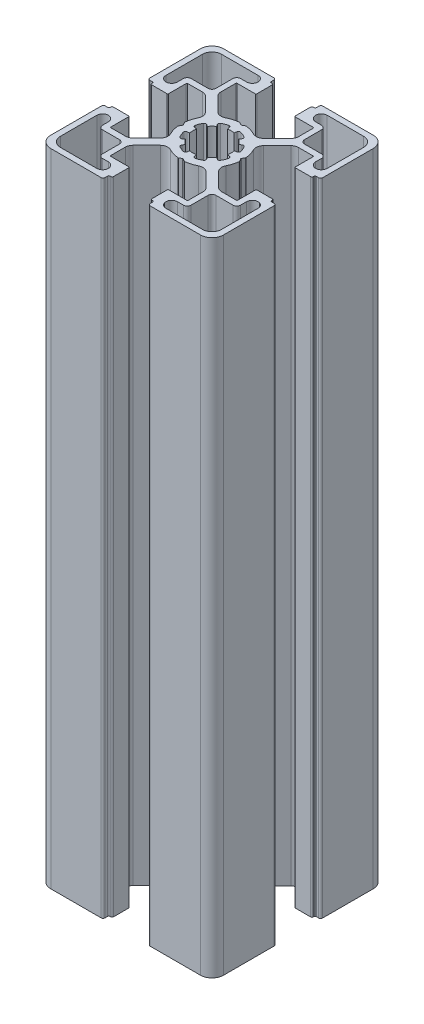
SolidWorks part; units mm, degrees
ref_plane "Front Plane" through (0, 0, 0) normal (0, 0, 1) x (1, 0, 0)
ref_plane "Top Plane" through (0, 0, 0) normal (0, 1, 0) x (1, 0, 0)
ref_plane "Right Plane" through (0, 0, 0) normal (1, 0, 0) x (0, 0, -1)
sketch "Sketch1" plane through (0, 0, 0) normal (0, 1, 0) x (1, 0, 0)
  line L106 (-18, 9.0002) -> (-18, 10.55)
  line L107 (-21, 18.5) -> (-21, 9.0002)
  line L108 (-9, 21) -> (-18.5, 21)
  line L109 (-10.55, 18) -> (-9, 18)
  line L110 (0.9675, 5.4811) -> (0.8674, 4.9242)
  line L111 (2.864, 4.0985) -> (3.1913, 4.5626)
  line L112 (4.5668, 3.2081) -> (4.0897, 2.8765)
  line L113 (4.9205, 0.8878) -> (5.4897, 0.9862)
  line L114 (5.4898, -0.9862) -> (4.9205, -0.8878)
  line L115 (4.0897, -2.8765) -> (4.5668, -3.2082)
  line L116 (3.1914, -4.5627) -> (2.864, -4.0985)
  line L117 (0.8674, -4.9242) -> (0.9675, -5.4811)
  line L118 (-0.9675, -5.4811) -> (-0.8674, -4.9242)
  line L119 (-2.864, -4.0985) -> (-3.1913, -4.5626)
  line L120 (-4.5668, -3.2082) -> (-4.0897, -2.8765)
  line L121 (-4.9205, -0.8878) -> (-5.4897, -0.9862)
  line L122 (-5.4899, 0.9862) -> (-4.9205, 0.8878)
  line L123 (-4.0897, 2.8765) -> (-4.5668, 3.2081)
  line L124 (-3.1914, 4.5627) -> (-2.864, 4.0985)
  line L125 (-0.8674, 4.9242) -> (-0.9675, 5.4811)
  line L126 (-11.55, 12.55) -> (-11.55, 17)
  line L127 (-17, 11.55) -> (-12.55, 11.55)
  line L128 (-21, -9.0002) -> (-21, -18.5)
  line L129 (-18, -10.55) -> (-18, -9.0002)
  line L130 (-12.55, -11.55) -> (-17, -11.55)
  line L131 (-11.55, -17) -> (-11.55, -12.55)
  line L132 (-9, -18) -> (-10.55, -18)
  line L133 (-18.5, -21) -> (-9, -21)
  line L134 (21, 9.0002) -> (21, 18.5)
  line L135 (18, 10.55) -> (18, 9.0002)
  line L136 (12.55, 11.55) -> (17, 11.55)
  line L137 (11.55, 17) -> (11.55, 12.55)
  line L138 (9, 18) -> (10.55, 18)
  line L139 (18.5, 21) -> (9, 21)
  line L140 (17, -11.55) -> (12.55, -11.55)
  line L141 (18, -9.0002) -> (18, -10.55)
  line L142 (21, -18.5) -> (21, -9.0002)
  line L143 (9, -21) -> (18.5, -21)
  line L144 (10.55, -18) -> (9, -18)
  line L145 (11.55, -12.55) -> (11.55, -17)
  line L146 (7.5635, 5.8587) -> (11.1298, 9.425)
  line L147 (12.5048, 9.9945) -> (16.3169, 9.9945)
  line L148 (16.5169, 9.7945) -> (16.5169, 5.2)
  line L149 (16.7169, 5) -> (20.7196, 5)
  line L150 (21.0196, 5.3) -> (21.0196, 5.5)
  line L151 (21.3196, 5.8) -> (22, 5.8)
  line L152 (22.5, 6.3) -> (22.5, 19.5)
  line L153 (19.5, 22.5) -> (6.3757, 22.5)
  line L154 (5.8757, 22) -> (5.8757, 21.3)
  line L155 (5.5757, 21) -> (5.3, 21)
  line L156 (5, 20.7) -> (5, 16.6668)
  line L157 (5.2, 16.4668) -> (9.9054, 16.4668)
  line L158 (10.1054, 16.2668) -> (10.1054, 12.4716)
  line L159 (9.5196, 11.0574) -> (5.9449, 7.4827)
  line L160 (0.7548, 7.9748) -> (0.1126, 7.6069)
  line L161 (-0.1126, 7.6069) -> (-0.7547, 7.9748)
  line L162 (-5.9449, 7.4827) -> (-9.5196, 11.0574)
  line L163 (-10.1054, 12.4716) -> (-10.1054, 16.2668)
  line L164 (-9.9054, 16.4668) -> (-5.2, 16.4668)
  line L165 (-5, 16.6668) -> (-5, 20.7)
  line L166 (-5.3, 21) -> (-5.5757, 21)
  line L167 (-5.8757, 21.3) -> (-5.8757, 22)
  line L168 (-6.3757, 22.5) -> (-19.5, 22.5)
  line L169 (-22.5, 19.5) -> (-22.5, 6.3)
  line L170 (-22, 5.8) -> (-21.3196, 5.8)
  line L171 (-21.0196, 5.5) -> (-21.0196, 5.3)
  line L172 (-20.7196, 5) -> (-16.7169, 5)
  line L173 (-16.5169, 5.2) -> (-16.5169, 9.7945)
  line L174 (-16.3169, 9.9945) -> (-12.5048, 9.9945)
  line L175 (-11.1298, 9.425) -> (-7.5635, 5.8587)
  line L176 (-7.974, 0.7926) -> (-7.5401, 0.0468)
  line L177 (-7.5401, -0.0468) -> (-7.974, -0.7926)
  line L178 (-7.5635, -5.8587) -> (-11.1298, -9.425)
  line L179 (-12.5048, -9.9945) -> (-16.3169, -9.9945)
  line L180 (-16.5169, -9.7945) -> (-16.5169, -5.2)
  line L181 (-16.7169, -5) -> (-20.7196, -5)
  line L182 (-21.0196, -5.3) -> (-21.0196, -5.5)
  line L183 (-21.3196, -5.8) -> (-22, -5.8)
  line L184 (-22.5, -6.3) -> (-22.5, -19.5)
  line L185 (-19.5, -22.5) -> (-6.3757, -22.5)
  line L186 (-5.8757, -22) -> (-5.8757, -21.3)
  line L187 (-5.5757, -21) -> (-5.3, -21)
  line L188 (-5, -20.7) -> (-5, -16.6668)
  line L189 (-5.2, -16.4668) -> (-9.9054, -16.4668)
  line L190 (-10.1054, -16.2668) -> (-10.1054, -12.4716)
  line L191 (-9.5196, -11.0574) -> (-5.9449, -7.4827)
  line L192 (-0.7547, -7.9748) -> (-0.1126, -7.6069)
  line L193 (0.1126, -7.6069) -> (0.7548, -7.9748)
  line L194 (5.9449, -7.4827) -> (9.5196, -11.0574)
  line L195 (10.1054, -12.4716) -> (10.1054, -16.2668)
  line L196 (9.9054, -16.4668) -> (5.2, -16.4668)
  line L197 (5, -16.6668) -> (5, -20.7)
  line L198 (5.3, -21) -> (5.5757, -21)
  line L199 (5.8757, -21.3) -> (5.8757, -22)
  line L200 (6.3757, -22.5) -> (19.5, -22.5)
  line L201 (22.5, -19.5) -> (22.5, -6.3)
  line L202 (22, -5.8) -> (21.3196, -5.8)
  line L203 (21.0196, -5.5) -> (21.0196, -5.3)
  line L204 (20.7196, -5) -> (16.7169, -5)
  line L205 (16.5169, -5.2) -> (16.5169, -9.7945)
  line L206 (16.3169, -9.9945) -> (12.5048, -9.9945)
  line L207 (11.1298, -9.425) -> (7.5635, -5.8587)
  line L208 (7.974, -0.7926) -> (7.5401, -0.0468)
  line L209 (7.5401, 0.0468) -> (7.974, 0.7926)
  arc A140 (-17, 11.55) -> (-18, 10.55) centre (-17, 10.55) ccw
  arc A141 (-21, 9.0002) -> (-18, 9.0002) centre (-19.5, 9.0002) ccw
  arc A142 (-18.5, 21) -> (-21, 18.5) centre (-18.5, 18.5) ccw
  arc A143 (-9, 18) -> (-9, 21) centre (-9, 19.5) ccw
  arc A144 (-10.55, 18) -> (-11.55, 17) centre (-10.55, 17) ccw
  arc A145 (-12.55, 11.55) -> (-11.55, 12.55) centre (-12.55, 12.55) ccw
  arc A146 (-21, -18.5) -> (-18.5, -21) centre (-18.5, -18.5) ccw
  arc A147 (-18, -9.0002) -> (-21, -9.0002) centre (-19.5, -9.0002) ccw
  arc A148 (-18, -10.55) -> (-17, -11.55) centre (-17, -10.55) ccw
  arc A149 (-11.55, -12.55) -> (-12.55, -11.55) centre (-12.55, -12.55) ccw
  arc A150 (-11.55, -17) -> (-10.55, -18) centre (-10.55, -17) ccw
  arc A151 (-9, -21) -> (-9, -18) centre (-9, -19.5) ccw
  arc A152 (0.8674, 4.9242) -> (-0.8674, 4.9242) centre (0, 0) ccw
  arc A153 (1.5951, 5.8941) -> (0.9675, 5.4811) centre (1.4627, 5.4119) ccw
  arc A154 (3.0417, 5.301) -> (1.5951, 5.8941) centre (0.0235, 0) ccw
  arc A155 (3.1913, 4.5626) -> (3.0417, 5.301) centre (2.7943, 4.8665) ccw
  arc A156 (4.0897, 2.8765) -> (2.864, 4.0985) centre (0, 0) ccw
  arc A157 (5.3025, 3.0565) -> (4.5668, 3.2081) centre (4.868, 2.8091) ccw
  arc A158 (5.906, 1.6142) -> (5.3025, 3.0565) centre (0.0235, 0) ccw
  arc A159 (5.4897, 0.9862) -> (5.906, 1.6142) centre (5.4239, 1.4819) ccw
  arc A160 (4.9205, -0.8878) -> (4.9205, 0.8878) centre (0, 0) ccw
  arc A161 (5.906, -1.6142) -> (5.4898, -0.9862) centre (5.4239, -1.4819) ccw
  arc A162 (5.3025, -3.0564) -> (5.906, -1.6142) centre (0.0235, 0) ccw
  arc A163 (4.5668, -3.2082) -> (5.3025, -3.0564) centre (4.868, -2.8091) ccw
  arc A164 (2.864, -4.0985) -> (4.0897, -2.8765) centre (0, 0) ccw
  arc A165 (3.0416, -5.301) -> (3.1914, -4.5627) centre (2.7943, -4.8665) ccw
  arc A166 (1.5951, -5.8941) -> (3.0416, -5.301) centre (0.0235, 0) ccw
  arc A167 (0.9675, -5.4811) -> (1.5951, -5.8941) centre (1.4627, -5.4119) ccw
  arc A168 (-0.8674, -4.9242) -> (0.8674, -4.9242) centre (0, 0) ccw
  arc A169 (-1.5951, -5.8941) -> (-0.9675, -5.4811) centre (-1.4627, -5.4119) ccw
  arc A170 (-3.0416, -5.301) -> (-1.5951, -5.8941) centre (-0.0235, 0) ccw
  arc A171 (-3.1913, -4.5626) -> (-3.0416, -5.301) centre (-2.7943, -4.8665) ccw
  arc A172 (-4.0897, -2.8765) -> (-2.864, -4.0985) centre (0, 0) ccw
  arc A173 (-5.3025, -3.0565) -> (-4.5668, -3.2082) centre (-4.868, -2.8091) ccw
  arc A174 (-5.906, -1.6142) -> (-5.3025, -3.0565) centre (-0.0235, 0) ccw
  arc A175 (-5.4897, -0.9862) -> (-5.906, -1.6142) centre (-5.4239, -1.4819) ccw
  arc A176 (-4.9205, 0.8878) -> (-4.9205, -0.8878) centre (0, 0) ccw
  arc A177 (-5.906, 1.6141) -> (-5.4899, 0.9862) centre (-5.4239, 1.4818) ccw
  arc A178 (-5.3025, 3.0564) -> (-5.906, 1.6141) centre (-0.0235, 0) ccw
  arc A179 (-4.5668, 3.2081) -> (-5.3025, 3.0564) centre (-4.868, 2.8091) ccw
  arc A180 (-2.864, 4.0985) -> (-4.0897, 2.8765) centre (0, 0) ccw
  arc A181 (-3.0417, 5.301) -> (-3.1914, 4.5627) centre (-2.7943, 4.8665) ccw
  arc A182 (-1.5951, 5.8941) -> (-3.0417, 5.301) centre (-0.0235, 0) ccw
  arc A183 (-0.9675, 5.4811) -> (-1.5951, 5.8941) centre (-1.4627, 5.4119) ccw
  arc A184 (21, 18.5) -> (18.5, 21) centre (18.5, 18.5) ccw
  arc A185 (18, 9.0002) -> (21, 9.0002) centre (19.5, 9.0002) ccw
  arc A186 (18, 10.55) -> (17, 11.55) centre (17, 10.55) ccw
  arc A187 (11.55, 12.55) -> (12.55, 11.55) centre (12.55, 12.55) ccw
  arc A188 (11.55, 17) -> (10.55, 18) centre (10.55, 17) ccw
  arc A189 (9, 21) -> (9, 18) centre (9, 19.5) ccw
  arc A190 (12.55, -11.55) -> (11.55, -12.55) centre (12.55, -12.55) ccw
  arc A191 (17, -11.55) -> (18, -10.55) centre (17, -10.55) ccw
  arc A192 (21, -9.0002) -> (18, -9.0002) centre (19.5, -9.0002) ccw
  arc A193 (18.5, -21) -> (21, -18.5) centre (18.5, -18.5) ccw
  arc A194 (9, -18) -> (9, -21) centre (9, -19.5) ccw
  arc A195 (10.55, -18) -> (11.55, -17) centre (10.55, -17) ccw
  arc A196 (7.9999, 0.9154) -> (7.2004, 3.6119) centre (0.0496, 0.0249) ccw
  arc A197 (7.5635, 5.8587) -> (7.2004, 3.6119) centre (8.9385, 4.4837) ccw
  arc A198 (12.5048, 9.9945) -> (11.1298, 9.425) centre (12.5048, 8.05) ccw
  arc A199 (16.5169, 9.7945) -> (16.3169, 9.9945) centre (16.3169, 9.7945) ccw
  arc A200 (16.5169, 5.2) -> (16.7169, 5) centre (16.7169, 5.2) ccw
  arc A201 (20.7196, 5) -> (21.0196, 5.3) centre (20.7196, 5.3) ccw
  arc A202 (21.3196, 5.8) -> (21.0196, 5.5) centre (21.3196, 5.5) ccw
  arc A203 (22, 5.8) -> (22.5, 6.3) centre (22, 6.3) ccw
  arc A204 (22.5, 19.5) -> (19.5, 22.5) centre (19.5, 19.5) ccw
  arc A205 (6.3757, 22.5) -> (5.8757, 22) centre (6.3757, 22) ccw
  arc A206 (5.5757, 21) -> (5.8757, 21.3) centre (5.5757, 21.3) ccw
  arc A207 (5.3, 21) -> (5, 20.7) centre (5.3, 20.7) ccw
  arc A208 (5, 16.6668) -> (5.2, 16.4668) centre (5.2, 16.6668) ccw
  arc A209 (10.1054, 16.2668) -> (9.9054, 16.4668) centre (9.9054, 16.2668) ccw
  arc A210 (9.5196, 11.0574) -> (10.1054, 12.4716) centre (8.1054, 12.4716) ccw
  arc A211 (3.6665, 7.1733) -> (5.9449, 7.4827) centre (4.5855, 8.9496) ccw
  arc A212 (3.6665, 7.1733) -> (0.8753, 8.0001) centre (0.0235, 0) ccw
  arc A213 (0.8753, 8.0001) -> (0.7548, 7.9748) centre (0.8542, 7.8013) ccw
  arc A214 (0, 7.531) -> (0.1126, 7.6069) centre (-0.0489, 7.7249) ccw
  arc A215 (-0.1126, 7.6069) -> (0, 7.531) centre (0.0489, 7.7249) ccw
  arc A216 (-0.7547, 7.9748) -> (-0.8753, 8.0001) centre (-0.8542, 7.8013) ccw
  arc A217 (-0.8753, 8.0001) -> (-3.6665, 7.1733) centre (-0.0235, 0) ccw
  arc A218 (-5.9449, 7.4827) -> (-3.6665, 7.1733) centre (-4.5855, 8.9496) ccw
  arc A219 (-10.1054, 12.4716) -> (-9.5196, 11.0574) centre (-8.1054, 12.4716) ccw
  arc A220 (-9.9054, 16.4668) -> (-10.1054, 16.2668) centre (-9.9054, 16.2668) ccw
  arc A221 (-5.2, 16.4668) -> (-5, 16.6668) centre (-5.2, 16.6668) ccw
  arc A222 (-5, 20.7) -> (-5.3, 21) centre (-5.3, 20.7) ccw
  arc A223 (-5.8757, 21.3) -> (-5.5757, 21) centre (-5.5757, 21.3) ccw
  arc A224 (-5.8757, 22) -> (-6.3757, 22.5) centre (-6.3757, 22) ccw
  arc A225 (-19.5, 22.5) -> (-22.5, 19.5) centre (-19.5, 19.5) ccw
  arc A226 (-22.5, 6.3) -> (-22, 5.8) centre (-22, 6.3) ccw
  arc A227 (-21.0196, 5.5) -> (-21.3196, 5.8) centre (-21.3196, 5.5) ccw
  arc A228 (-21.0196, 5.3) -> (-20.7196, 5) centre (-20.7196, 5.3) ccw
  arc A229 (-16.7169, 5) -> (-16.5169, 5.2) centre (-16.7169, 5.2) ccw
  arc A230 (-16.3169, 9.9945) -> (-16.5169, 9.7945) centre (-16.3169, 9.7945) ccw
  arc A231 (-11.1298, 9.425) -> (-12.5048, 9.9945) centre (-12.5048, 8.05) ccw
  arc A232 (-7.2004, 3.6119) -> (-7.5635, 5.8587) centre (-8.9385, 4.4837) ccw
  arc A233 (-7.2004, 3.6119) -> (-7.9999, 0.9154) centre (-0.0496, 0.0249) ccw
  arc A234 (-7.9999, 0.9154) -> (-7.974, 0.7926) centre (-7.8011, 0.8932) ccw
  arc A235 (-7.5313, 0) -> (-7.5401, 0.0468) centre (-7.7309, -0.013) ccw
  arc A236 (-7.5401, -0.0468) -> (-7.5313, 0) centre (-7.7309, 0.013) ccw
  arc A237 (-7.974, -0.7926) -> (-7.9999, -0.9154) centre (-7.8011, -0.8932) ccw
  arc A238 (-7.9999, -0.9154) -> (-7.2004, -3.6119) centre (-0.0496, -0.0249) ccw
  arc A239 (-7.5635, -5.8587) -> (-7.2004, -3.6119) centre (-8.9385, -4.4837) ccw
  arc A240 (-12.5048, -9.9945) -> (-11.1298, -9.425) centre (-12.5048, -8.05) ccw
  arc A241 (-16.5169, -9.7945) -> (-16.3169, -9.9945) centre (-16.3169, -9.7945) ccw
  arc A242 (-16.5169, -5.2) -> (-16.7169, -5) centre (-16.7169, -5.2) ccw
  arc A243 (-20.7196, -5) -> (-21.0196, -5.3) centre (-20.7196, -5.3) ccw
  arc A244 (-21.3196, -5.8) -> (-21.0196, -5.5) centre (-21.3196, -5.5) ccw
  arc A245 (-22, -5.8) -> (-22.5, -6.3) centre (-22, -6.3) ccw
  arc A246 (-22.5, -19.5) -> (-19.5, -22.5) centre (-19.5, -19.5) ccw
  arc A247 (-6.3757, -22.5) -> (-5.8757, -22) centre (-6.3757, -22) ccw
  arc A248 (-5.5757, -21) -> (-5.8757, -21.3) centre (-5.5757, -21.3) ccw
  arc A249 (-5.3, -21) -> (-5, -20.7) centre (-5.3, -20.7) ccw
  arc A250 (-5, -16.6668) -> (-5.2, -16.4668) centre (-5.2, -16.6668) ccw
  arc A251 (-10.1054, -16.2668) -> (-9.9054, -16.4668) centre (-9.9054, -16.2668) ccw
  arc A252 (-9.5196, -11.0574) -> (-10.1054, -12.4716) centre (-8.1054, -12.4716) ccw
  arc A253 (-3.6665, -7.1733) -> (-5.9449, -7.4827) centre (-4.5855, -8.9496) ccw
  arc A254 (-3.6665, -7.1733) -> (-0.8753, -8.0001) centre (-0.0235, 0) ccw
  arc A255 (-0.8753, -8.0001) -> (-0.7547, -7.9748) centre (-0.8542, -7.8013) ccw
  arc A256 (0, -7.531) -> (-0.1126, -7.6069) centre (0.0489, -7.7249) ccw
  arc A257 (0.1126, -7.6069) -> (0, -7.531) centre (-0.0489, -7.7249) ccw
  arc A258 (0.7548, -7.9748) -> (0.8753, -8.0001) centre (0.8542, -7.8012) ccw
  arc A259 (0.8753, -8.0001) -> (3.6665, -7.1733) centre (0.0235, 0) ccw
  arc A260 (5.9449, -7.4827) -> (3.6665, -7.1733) centre (4.5855, -8.9496) ccw
  arc A261 (10.1054, -12.4716) -> (9.5196, -11.0574) centre (8.1054, -12.4716) ccw
  arc A262 (9.9054, -16.4668) -> (10.1054, -16.2668) centre (9.9054, -16.2668) ccw
  arc A263 (5.2, -16.4668) -> (5, -16.6668) centre (5.2, -16.6668) ccw
  arc A264 (5, -20.7) -> (5.3, -21) centre (5.3, -20.7) ccw
  arc A265 (5.8757, -21.3) -> (5.5757, -21) centre (5.5757, -21.3) ccw
  arc A266 (5.8757, -22) -> (6.3757, -22.5) centre (6.3757, -22) ccw
  arc A267 (19.5, -22.5) -> (22.5, -19.5) centre (19.5, -19.5) ccw
  arc A268 (22.5, -6.3) -> (22, -5.8) centre (22, -6.3) ccw
  arc A269 (21.0196, -5.5) -> (21.3196, -5.8) centre (21.3196, -5.5) ccw
  arc A270 (21.0196, -5.3) -> (20.7196, -5) centre (20.7196, -5.3) ccw
  arc A271 (16.7169, -5) -> (16.5169, -5.2) centre (16.7169, -5.2) ccw
  arc A272 (16.3169, -9.9945) -> (16.5169, -9.7945) centre (16.3169, -9.7945) ccw
  arc A273 (11.1298, -9.425) -> (12.5048, -9.9945) centre (12.5048, -8.05) ccw
  arc A274 (7.2004, -3.6119) -> (7.5635, -5.8587) centre (8.9385, -4.4837) ccw
  arc A275 (7.2004, -3.6119) -> (7.9999, -0.9154) centre (0.0496, -0.0249) ccw
  arc A276 (7.9999, -0.9154) -> (7.974, -0.7926) centre (7.8011, -0.8932) ccw
  arc A277 (7.5313, 0) -> (7.5401, -0.0468) centre (7.7309, 0.013) ccw
  arc A278 (7.5401, 0.0468) -> (7.5313, 0) centre (7.7309, -0.013) ccw
  arc A279 (7.974, 0.7926) -> (7.9999, 0.9154) centre (7.8011, 0.8932) ccw
extrude "Boss-Extrude1" add sketch "Sketch1" along normal blind 167
